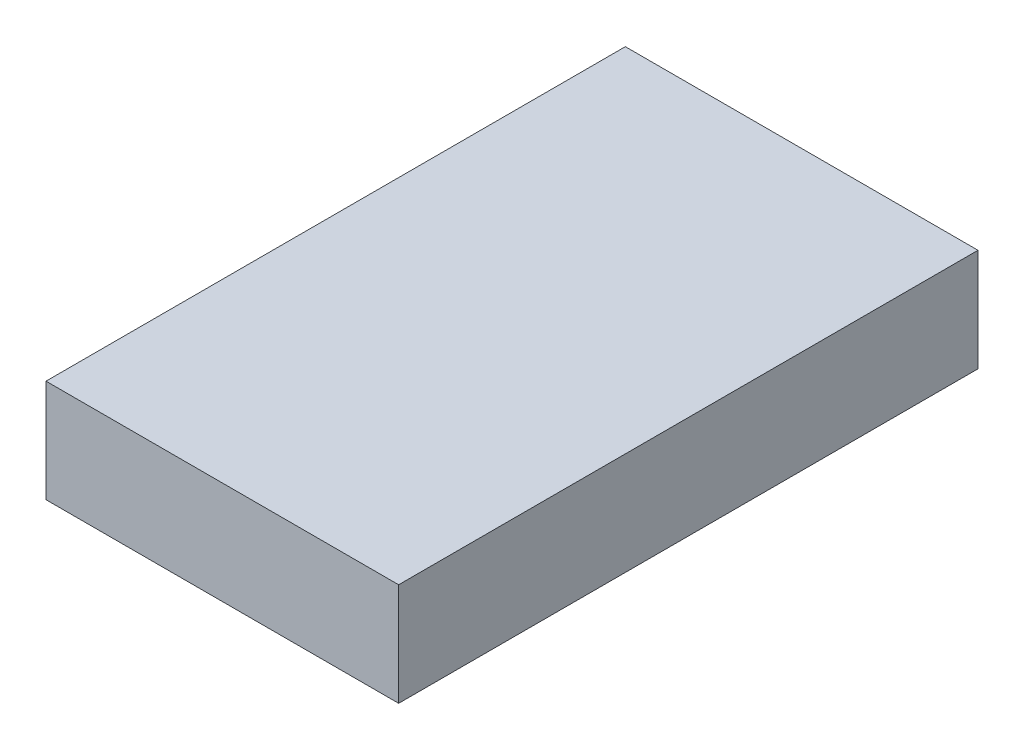
SolidWorks part; units mm, degrees
ref_plane "Front Plane" through (0, 0, 0) normal (0, 0, 1) x (1, 0, 0)
ref_plane "Top Plane" through (0, 0, 0) normal (0, 1, 0) x (1, 0, 0)
ref_plane "Right Plane" through (0, 0, 0) normal (1, 0, 0) x (0, 0, -1)
sketch "Sketch1" plane through (0, 0, 0) normal (0, 1, 0) x (1, 0, 0)
  line L1 (-9.1, -14.95) -> (9.1, -14.95)
  line L2 (-9.1, -14.95) -> (-9.1, 14.95)
  line L3 (-9.1, 14.95) -> (9.1, 14.95)
  line L4 (9.1, -14.95) -> (9.1, 14.95)
  line L5 (-9.1, -14.95) -> (9.1, 14.95) construction
  line L6 (-9.1, 14.95) -> (9.1, -14.95) construction
  point P0 (0, 0)
  dimension "D1" = 29.9
  dimension "D2" = 18.2
extrude "Boss-Extrude1" add sketch "Sketch1" along normal blind 5.3
